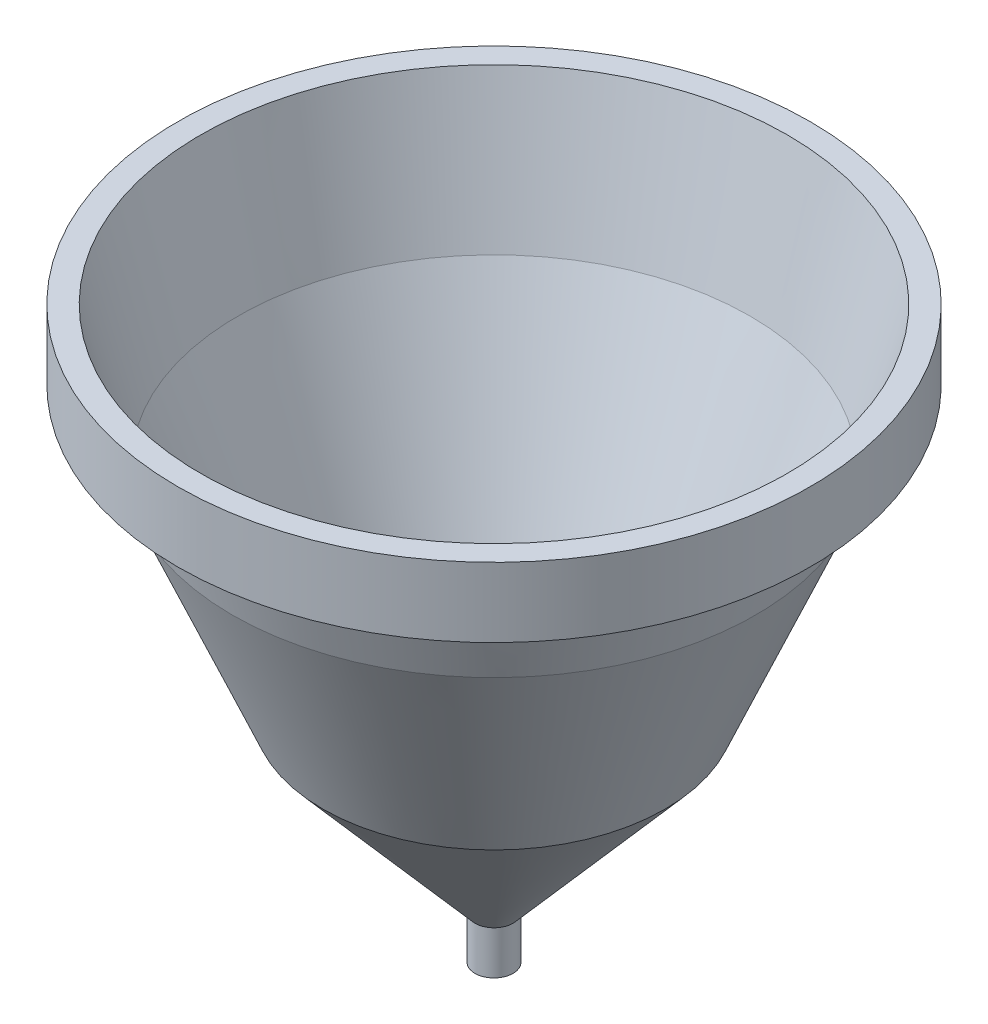
SolidWorks part; units mm, degrees
ref_plane "Piano frontale" through (0, 0, 0) normal (0, 0, 1) x (1, 0, 0)
ref_plane "Piano superiore" through (0, 0, 0) normal (0, 1, 0) x (1, 0, 0)
ref_plane "Piano destro" through (0, 0, 0) normal (1, 0, 0) x (0, 0, -1)
sketch "Schizzo1" plane through (0, 0, 0) normal (1, 0, 0) x (0, 0, -1)
  line L2 (-68.6088, 179.5623) -> (-76.6088, 179.5623) construction
  line L3 (-68.6088, 179.5623) -> (-68.6088, 145.7549) construction
  line L5 (-68.6088, 179.5623) -> (-59.5501, 145.7549)
  line L6 (-76.6088, 179.5623) -> (-68.6088, 179.5623)
  line L7 (-76.6088, 179.5623) -> (-76.6088, 169.5623)
  line L8 (-76.6088, 169.5623) -> (-78.4088, 169.5623)
  line L9 (-78.4088, 169.5623) -> (-78.4088, 193.5623)
  line L10 (-66.8722, 180.0276) -> (-70.4988, 193.5623)
  line L11 (-66.8722, 180.0276) -> (-57.6888, 145.7549)
  line L12 (-57.6888, 145.7549) -> (-26.7145, 72.784)
  line L13 (-66.8722, 180.0276) -> (-80.3487, 230.3226) construction
  line L14 (-68.6088, 179.5623) -> (-82.0853, 229.8572) construction
  line L15 (-68.6088, 145.7549) -> (-57.6888, 145.7549) construction
  line L16 (-66.8722, 180.0276) -> (-50.5181, 118.9932) construction
  line L17 (-68.6088, 179.5623) -> (-52.2547, 118.5279) construction
  line L18 (-59.5501, 145.7549) -> (-28.2916, 72.1145)
  line L23 (-28.2916, 72.1145) -> (24.1931, 11.7377)
  line L24 (-26.7145, 72.784) -> (25.7702, 12.4072)
  line L25 (-70.4988, 193.5623) -> (-78.4088, 193.5623)
  line L26 (-28.2916, 72.1145) -> (-28.2916, 23.1434) construction
  line L27 (-28.2916, 72.1145) -> (-26.7145, 72.784)
  line L28 (30.7702, -3.3928) -> (30.7702, 196.6072) construction
  line L29 (-59.5501, 145.7549) -> (-59.5501, 57.6891) construction
  line L30 (24.1931, 11.7377) -> (24.1931, -3.2623)
  line L31 (25.7702, 12.4072) -> (25.7702, -3.3928)
  line L32 (24.1931, -3.2623) -> (25.7702, -3.3928)
  dimension "D3" = 23
  dimension "D2" = 8
  dimension "D4" = 41
  dimension "D6" = 10
  dimension "D7" = 1.8
  dimension "D11" = 7.91
revolve "Rivoluzione1" add sketch "Schizzo1" angle 360 about L28
